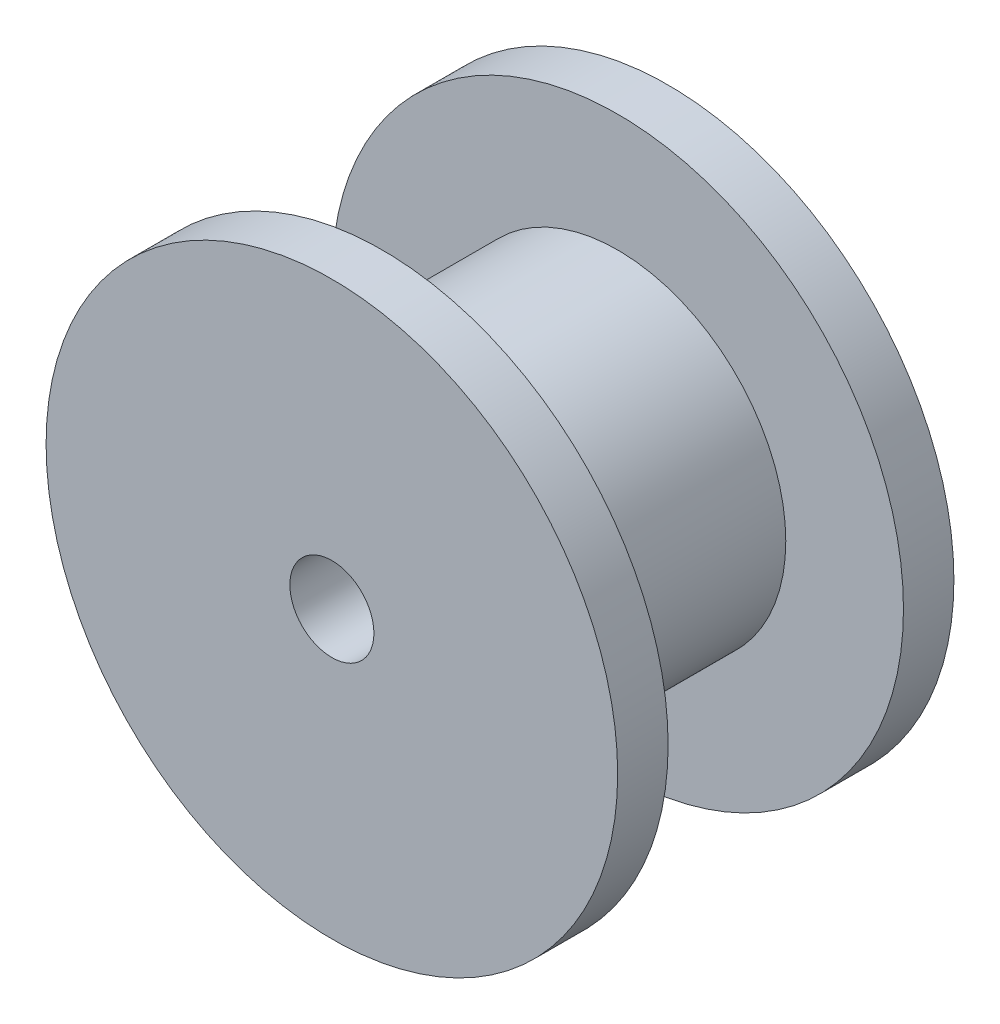
SolidWorks part; units mm, degrees
ref_plane "Alzado" through (0, 0, 0) normal (0, 0, 1) x (1, 0, 0)
ref_plane "Planta" through (0, 0, 0) normal (0, 1, 0) x (1, 0, 0)
ref_plane "Vista lateral" through (0, 0, 0) normal (1, 0, 0) x (0, 0, -1)
sketch "Sketch2" plane through (0, 0, 0) normal (0, 1, 0) x (1, 0, 0)
  line L0 (0, -198.4678) -> (0, 9724.922) construction
  line L1 (0, 10) -> (-8.5, 10)
  line L2 (-8.5, 10) -> (-8.5, 8.5)
  line L3 (-8.5, 8.5) -> (-5, 8.5)
  line L4 (-5, 8.5) -> (-5, 1.5)
  line L5 (-5, 1.5) -> (-8.5, 1.5)
  line L6 (-8.5, 1.5) -> (-8.5, 0)
  line L7 (-8.5, 0) -> (0, 0)
  line L8 (0, 10) -> (0, 0)
  dimension "D1" = 7
  dimension "D2" = 5
  dimension "D3" = 8.5
  dimension "D4" = 10
revolve "Revolve1" add sketch "Sketch2" angle 360 about L0
sketch "Sketch3" plane through (0, 0, 0) normal (0, 0, 1) x (1, 0, 0)
  circle A0 centre (0, 0) radius 1.7405
  point P0 (0, 0)
hole_wizard "Taladro roscado M2.52" positions "Sketch3" profile "Sketch4" tap size "M2.5" standard "ISO" end condition through all
sketch "Sketch4" plane through (0, 0, 0) normal (1, 0, 0) x (0, -1, 0)
  line L0 (0, 0) -> (0, 10)
  line L1 (0, 10) -> (1.25, 10)
  line L2 (1.25, 10) -> (1.25, 0)
  line L5 (1.25, 0) -> (0, 0)
  line L11 (0, -6.35) -> (0, 107.95) construction
  dimension "Diámetro mayor de rosca" = 2.5
  dimension "Profundidad de perforador para roscar hasta el siguiente" = 10
